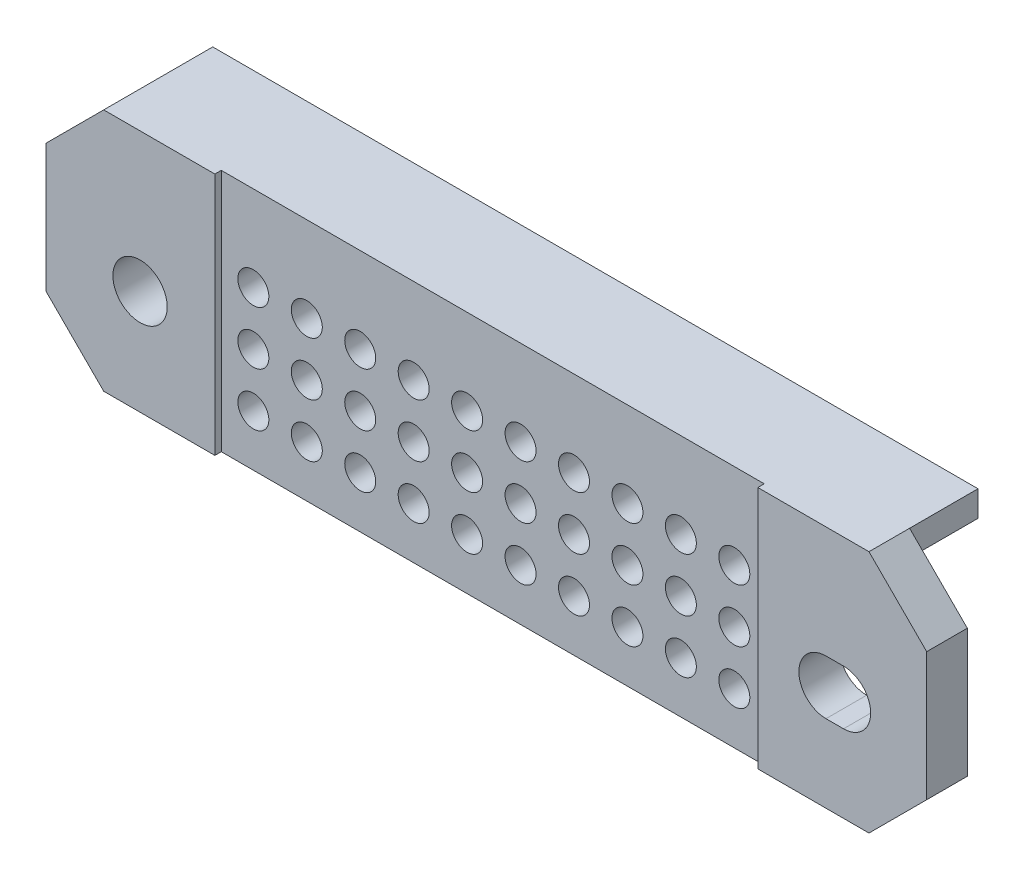
SolidWorks part; units mm, degrees
ref_plane "Front Plane" through (0, 0, 0) normal (0, 0, 1) x (1, 0, 0)
ref_plane "Top Plane" through (0, 0, 0) normal (0, 1, 0) x (1, 0, 0)
ref_plane "Right Plane" through (0, 0, 0) normal (1, 0, 0) x (0, 0, -1)
sketch "Sketch1" plane through (0, 0, 0) normal (0, 0, 1) x (1, 0, 0)
  line L0 (0, 3.429) -> (0, 11.049)
  line L1 (3.429, 14.478) -> (48.895, 14.478)
  line L2 (52.324, 11.049) -> (52.324, 3.429)
  line L3 (48.895, 0) -> (3.429, 0)
  line L4 (0, 11.049) -> (3.429, 14.478)
  line L5 (3.429, 0) -> (0, 3.429)
  line L6 (52.324, 3.429) -> (48.895, 0)
  line L7 (48.895, 14.478) -> (52.324, 11.049)
  point P0 (0, 0)
  point P1 (0, 14.478)
  point P3 (52.324, 14.478)
  point P5 (52.324, 0)
  dimension "D1" = 52.324
  dimension "D2" = 14.478
  dimension "D3" = 3.429
  dimension "D4" = 45
  dimension "D5" = 3.429
  dimension "D6" = 45
  dimension "D7" = 3.429
  dimension "D8" = 45
  dimension "D9" = 3.429
  dimension "D10" = 45
extrude "Boss-Extrude1" add sketch "Sketch1" along normal blind 2.032
sketch "Sketch2" plane through (0, 0, 2.032) normal (0, 0, 1) x (1, 0, 0)
  line L0 (0, 11.049) -> (0, 3.429)
  line L1 (0, 3.429) -> (3.429, 0) construction
  line L2 (0, 3.429) -> (3.429, 0)
  line L3 (3.429, 0) -> (10.033, 0)
  line L4 (3.429, 0) -> (48.895, 0) construction
  line L5 (10.033, 0) -> (10.033, 14.478)
  line L6 (48.895, 14.478) -> (3.429, 14.478) construction
  line L7 (10.033, 14.478) -> (3.429, 14.478)
  line L8 (3.429, 14.478) -> (0, 11.049)
  line L9 (42.291, 14.478) -> (42.291, 0)
  line L10 (42.291, 0) -> (48.895, 0)
  line L11 (48.895, 0) -> (52.324, 3.429)
  line L12 (52.324, 3.429) -> (52.324, 11.049)
  line L13 (52.324, 11.049) -> (48.895, 14.478)
  line L14 (48.895, 14.478) -> (42.291, 14.478)
  dimension "D1" = 32.258
  dimension "D2" = 10.033
extrude "Boss-Extrude2" add sketch "Sketch2" along normal blind 0.381
sketch "Sketch3" plane through (0, 0, 0) normal (0, 0, -1) x (-1, 0, 0)
  line L0 (-48.895, 14.478) -> (-3.429, 14.478) construction
  line L1 (-48.895, 14.478) -> (-3.429, 14.478)
  line L2 (-48.895, 14.478) -> (-48.895, 12.954)
  line L3 (-48.895, 12.954) -> (-3.429, 12.954)
  line L4 (-3.429, 14.478) -> (-3.429, 12.954)
  dimension "D1" = 1.524
extrude "Boss-Extrude3" add sketch "Sketch3" along normal blind 4.064
sketch "Sketch4" plane through (0, 0, 0) normal (0, 0, -1) x (-1, 0, 0)
  line L0 (-47.3837, 6.223) -> (-46.3423, 6.223) construction
  line L1 (-47.3837, 7.8359) -> (-46.3423, 7.8359)
  line L2 (-47.3837, 4.6101) -> (-46.3423, 4.6101)
  line L3 (-48.9966, 6.223) -> (-48.9966, 2.7195) construction
  line L4 (-44.7294, 6.223) -> (-44.7294, 2.7195) construction
  line L5 (0, 11.049) -> (0, 3.429) construction
  line L6 (-3.429, 0) -> (-48.895, 0) construction
  line L7 (-11.938, 3.048) -> (-15.113, 3.048) construction
  line L8 (-11.938, 3.048) -> (-11.938, 6.223) construction
  arc A0 (-47.3837, 7.8359) -> (-47.3837, 4.6101) centre (-47.3837, 6.223) ccw
  arc A1 (-46.3423, 4.6101) -> (-46.3423, 7.8359) centre (-46.3423, 6.223) ccw
  circle A2 centre (-5.588, 6.223) radius 1.6129
  circle A3 centre (-11.938, 3.048) radius 0.9207
  circle A4 centre (-15.113, 3.048) radius 0.9207
  circle A5 centre (-18.288, 3.048) radius 0.9207
  circle A6 centre (-21.463, 3.048) radius 0.9207
  circle A7 centre (-24.638, 3.048) radius 0.9207
  circle A8 centre (-27.813, 3.048) radius 0.9207
  circle A9 centre (-30.988, 3.048) radius 0.9207
  circle A10 centre (-34.163, 3.048) radius 0.9207
  circle A11 centre (-37.338, 3.048) radius 0.9207
  circle A12 centre (-40.513, 3.048) radius 0.9207
  circle A13 centre (-15.113, 6.223) radius 0.9207
  circle A14 centre (-18.288, 6.223) radius 0.9207
  circle A15 centre (-21.463, 6.223) radius 0.9208
  circle A16 centre (-24.638, 6.223) radius 0.9208
  circle A17 centre (-27.813, 6.223) radius 0.9208
  circle A18 centre (-30.988, 6.223) radius 0.9207
  circle A19 centre (-34.163, 6.223) radius 0.9207
  circle A20 centre (-37.338, 6.223) radius 0.9208
  circle A21 centre (-40.513, 6.223) radius 0.9208
  circle A22 centre (-15.113, 9.398) radius 0.9208
  circle A23 centre (-18.288, 9.398) radius 0.9208
  circle A24 centre (-21.463, 9.398) radius 0.9208
  circle A25 centre (-24.638, 9.398) radius 0.9208
  circle A26 centre (-27.813, 9.398) radius 0.9207
  circle A27 centre (-30.988, 9.398) radius 0.9208
  circle A28 centre (-34.163, 9.398) radius 0.9208
  circle A29 centre (-37.338, 9.398) radius 0.9207
  circle A30 centre (-40.513, 9.398) radius 0.9208
  circle A31 centre (-11.938, 6.223) radius 0.9208
  circle A32 centre (-11.938, 9.398) radius 0.9207
  point P2 (-46.863, 6.223)
  dimension "D2" = 3.2258
  dimension "D9" = 1.8415
  dimension "D1" = 3.2258
  dimension "D3" = 4.2672
  dimension "D4" = 41.275
  dimension "D5" = 5.588
  dimension "D6" = 6.223
  dimension "D7" = 6.35
  dimension "D8" = 3.175
  dimension "D12" = 90
  dimension "D13" = 3.175
  dimension "D14" = 3.175
  dimension "D10" = 10
  dimension "D11" = 3
extrude "Cut-Extrude1" cut sketch "Sketch4" against normal through all
